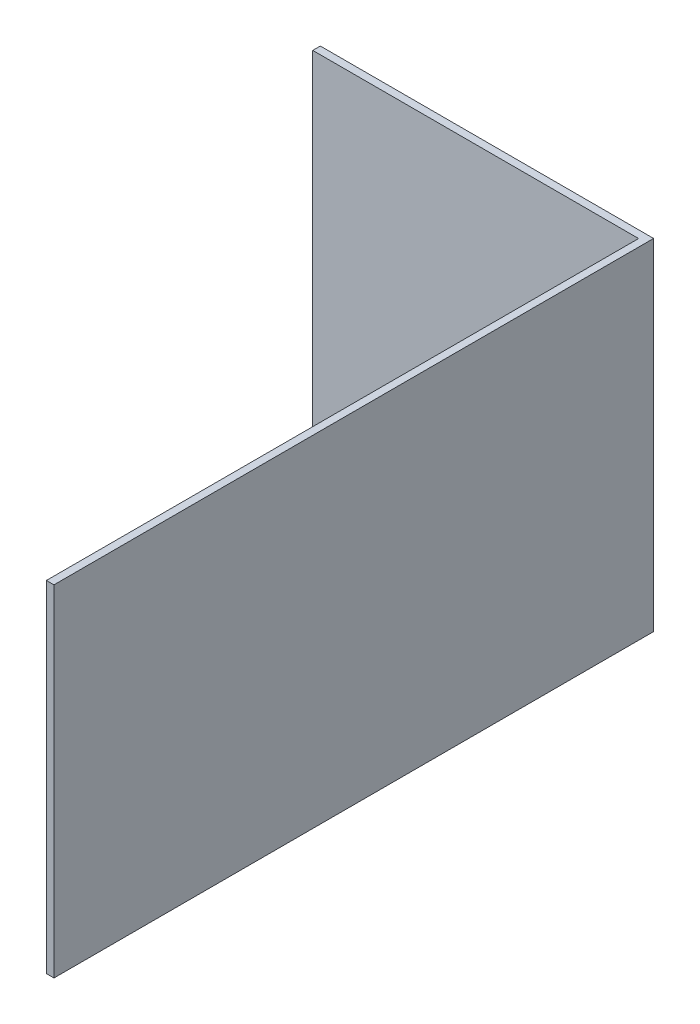
SolidWorks part; units mm, degrees
ref_plane "Front Plane" through (0, 0, 0) normal (0, 0, 1) x (1, 0, 0)
ref_plane "Top Plane" through (0, 0, 0) normal (0, 1, 0) x (1, 0, 0)
ref_plane "Right Plane" through (0, 0, 0) normal (1, 0, 0) x (0, 0, -1)
sketch "Sketch1" plane through (0, 0, 0) normal (0, 1, 0) x (1, 0, 0)
  line L1 (345.3109, -749.2863) -> (345.3109, 423.2106)
  line L2 (345.3109, 423.2106) -> (-299.88, 423.2106)
  line L3 (345.3109, -749.2863) -> (360.3109, -749.2863)
  line L4 (-299.88, 423.2106) -> (-299.88, 438.2106)
  line L5 (-299.88, 438.2106) -> (360, 438.2106)
  line L6 (360, 438.2106) -> (360.3109, -749.2863)
  dimension "D1" = 15
  dimension "D2" = 15
  dimension "D3" = 0.015
  dimension "D4" = 659.88
  dimension "D5" = 1187.497
  dimension "D6" = 423.2106
  dimension "D7" = 345.3109
  dimension "D8" = 360.1147
extrude "Boss-Extrude1" add sketch "Sketch1" along normal blind 674.1356
